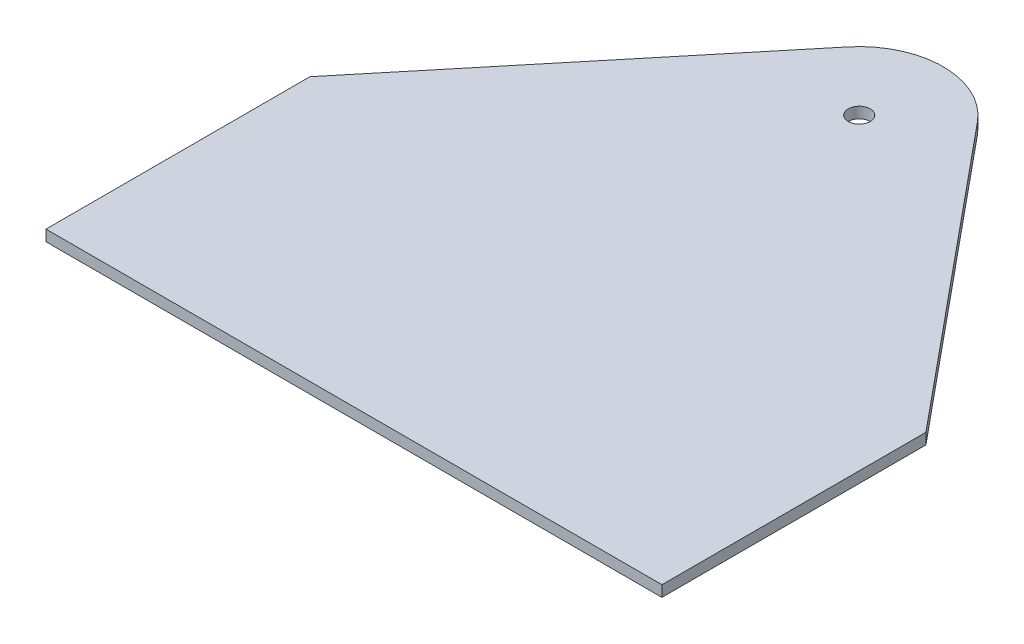
SolidWorks part; units mm, degrees
ref_plane "Front Plane" through (0, 0, 0) normal (0, 0, 1) x (1, 0, 0)
ref_plane "Top Plane" through (0, 0, 0) normal (0, 1, 0) x (1, 0, 0)
ref_plane "Right Plane" through (0, 0, 0) normal (1, 0, 0) x (0, 0, -1)
sketch "Sketch1" plane through (0, 0, 0) normal (0, 1, 0) x (1, 0, 0)
  line L0 (-88.9, 0) -> (88.9, 0)
  line L1 (-88.9, 38.1) -> (88.9, 38.1) construction
  line L2 (-88.9, 0) -> (-88.9, 76.2)
  line L3 (-88.9, 38.1) -> (0, 145.8631) construction
  line L8 (0, 145.8631) -> (88.9, 38.1) construction
  line L13 (88.9, 0) -> (88.9, 76.2)
  line L14 (-88.9, 76.2) -> (-18.7027, 161.292)
  line L15 (18.7027, 161.292) -> (88.9, 76.2)
  arc A0 (-18.7027, 161.292) -> (18.7027, 161.292) centre (0, 145.8631) cw
  circle A1 centre (0, 145.8631) radius 3.175
  point P4 (0, 0)
  dimension "D5" = 6.35
  dimension "D1" = 177.8
  dimension "D2" = 139.7
  dimension "D3" = 38.1
  dimension "D4" = 76.2
extrude "Boss-Extrude1" add sketch "Sketch1" along normal blind 3.175
